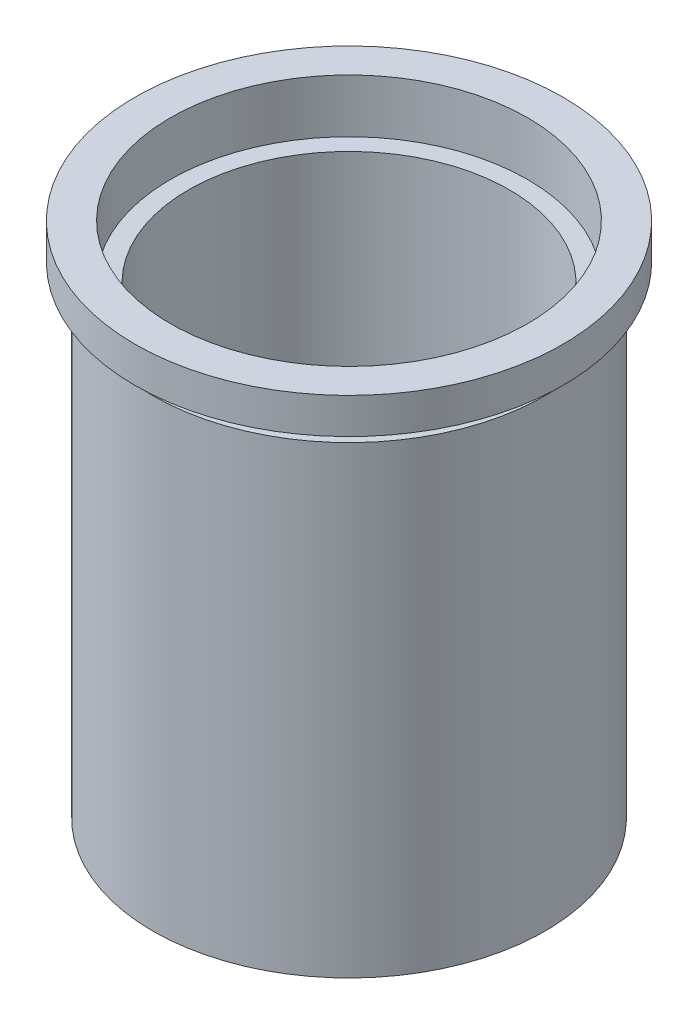
SolidWorks part; units mm, degrees
ref_plane "Спереди" through (0, 0, 0) normal (0, 0, 1) x (1, 0, 0)
ref_plane "Сверху" through (0, 0, 0) normal (0, 1, 0) x (1, 0, 0)
ref_plane "Справа" through (0, 0, 0) normal (1, 0, 0) x (0, 0, -1)
sketch "Эскиз2" plane through (0, 0, 0) normal (0, -1, 0) x (1, 0, 0)
  circle A0 centre (0, 0) radius 10.01
  circle A1 centre (0, 0) radius 9
extrude "Бобышка-Вытянуть2" add sketch "Эскиз2" along normal blind 25 separate body
sketch "Эскиз3" plane through (0, 0, 0) normal (0, 1, 0) x (1, 0, 0)
  circle A0 centre (0, 0) radius 10.01
extrude "Бобышка-Вытянуть3" add sketch "Эскиз3" along normal blind 2
sketch "Эскиз4" plane through (0, 2, 0) normal (0, 1, 0) x (1, 0, 0)
  circle A0 centre (0, 0) radius 9
extrude "Вырез-Вытянуть1" cut sketch "Эскиз4" against normal blind 1
sketch "Эскиз6" plane through (0, 1, 0) normal (0, 1, 0) x (1, 0, 0)
  circle A0 centre (0, 0) radius 8
extrude "Вырез-Вытянуть3" cut sketch "Эскиз6" against normal blind 3
sketch "Эскиз7" plane through (0, 1, 0) normal (0, 1, 0) x (1, 0, 0)
  circle A0 centre (0, 0) radius 11
  circle A1 centre (0, 0) radius 10
extrude "Бобышка-Вытянуть4" add sketch "Эскиз7" along normal blind 4
cosmetic thread "Условное изображение резьбы2"
sketch "Эскиз8" plane through (0, 0, 0) normal (0, -1, 0) x (1, 0, 0)
  circle A0 centre (0, 0) radius 8
  circle A1 centre (0, 0) radius 9
extrude "Бобышка-Вытянуть5" add sketch "Эскиз8" along normal blind 25
sketch "Эскиз10" plane through (0, 1, 0) normal (0, -1, 0) x (1, 0, 0)
  circle A0 centre (0, 0) radius 10.01
  circle A1 centre (0, 0) radius 9.5
extrude "Вырез-Вытянуть5" cut sketch "Эскиз10" along normal blind 1
sketch "Эскиз11" plane through (0, 1, 0) normal (0, 1, 0) x (1, 0, 0)
  circle A0 centre (0, 0) radius 10.01
extrude "Вырез-Вытянуть6" cut sketch "Эскиз11" along normal blind 10
sketch "Эскиз12" plane through (0, -25, 0) normal (0, -1, 0) x (1, 0, 0)
  circle A1 centre (0, 0) radius 10.01
  circle A2 centre (0, 0) radius 11
extrude "Бобышка-Вытянуть6" add sketch "Эскиз12" against normal blind 26
sketch "Эскиз13" plane through (0, 1, 0) normal (0, 1, 0) x (1, 0, 0)
  circle A0 centre (0, 0) radius 9
extrude "Вырез-Вытянуть7" cut sketch "Эскиз13" against normal blind 26
sketch "Эскиз14" plane through (0, 1, 0) normal (0, 1, 0) x (1, 0, 0)
  circle A0 centre (0, 0) radius 9.5
  circle A1 centre (0, 0) radius 10.0052
extrude "Бобышка-Вытянуть7" add sketch "Эскиз14" against normal blind 26
sketch "Эскиз16" plane through (0, 2, 0) normal (0, -1, 0) x (1, 0, 0)
  circle A0 centre (0, 0) radius 11
  circle A1 centre (0, 0) radius 10.5
extrude "Вырез-Вытянуть12" cut sketch "Эскиз16" along normal blind 1
sketch "Эскиз17" plane through (0, 5, 0) normal (0, 1, 0) x (1, 0, 0)
  circle A0 centre (0, 0) radius 13.7326
extrude "Вырез-Вытянуть13" cut sketch "Эскиз17" against normal blind 1
sketch "Эскиз19" plane through (0, 1, 0) normal (0, 1, 0) x (1, 0, 0)
  circle A0 centre (0, 0) radius 10.0052
  circle A1 centre (0, 0) radius 10.2294
extrude "Бобышка-Вытянуть10" add sketch "Эскиз19" against normal blind 10
sketch "Эскиз20" plane through (0, 4, 0) normal (0, 1, 0) x (1, 0, 0)
  circle A0 centre (0, 0) radius 11
  circle A1 centre (0, 0) radius 12
extrude "Бобышка-Вытянуть11" add sketch "Эскиз20" against normal blind 2
